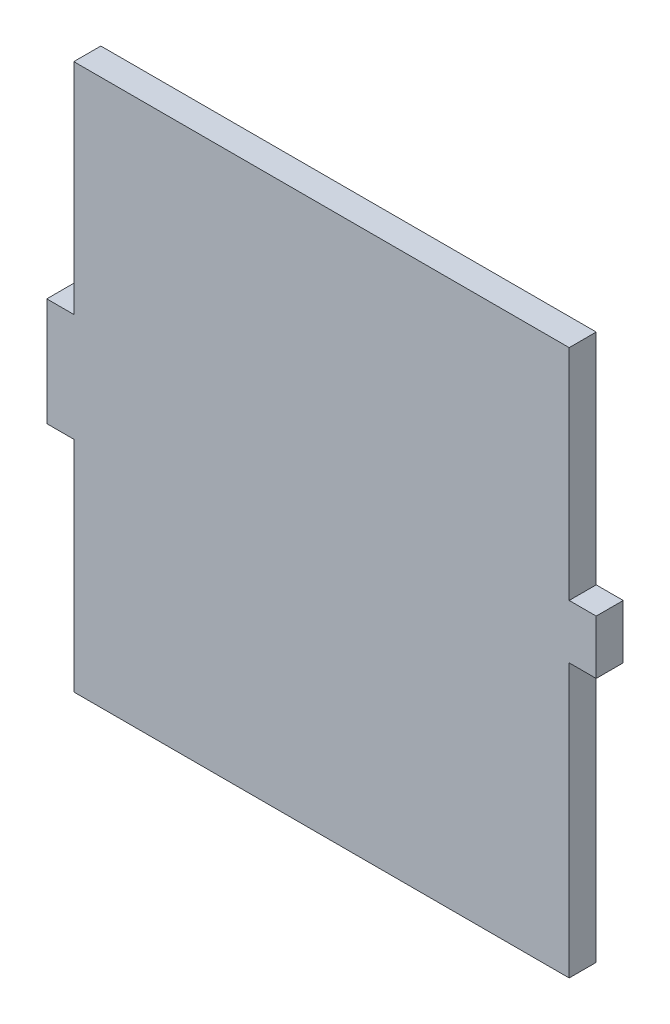
SolidWorks part; units mm, degrees
ref_plane "Přední rovina" through (0, 0, 0) normal (0, 0, 1) x (1, 0, 0)
ref_plane "Horní rovina" through (0, 0, 0) normal (0, 1, 0) x (1, 0, 0)
ref_plane "Pravá rovina" through (0, 0, 0) normal (1, 0, 0) x (0, 0, -1)
sketch "Skica1" plane through (0, 0, 0) normal (0, 0, 1) x (1, 0, 0)
  line L4 (55, -30.31) -> (55, -60.61)
  line L23 (0, 0) -> (55, 0)
  line L24 (0, 0) -> (0, -24.31)
  line L25 (0, -60.61) -> (55, -60.61)
  line L26 (55, 0) -> (55, -24.31)
  line L27 (0, -24.31) -> (-3, -24.31)
  line L29 (0, -36.31) -> (-3, -36.31)
  line L30 (-3, -24.31) -> (-3, -36.31)
  line L31 (55, -24.31) -> (58, -24.31)
  line L33 (55, -30.31) -> (58, -30.31)
  line L34 (58, -24.31) -> (58, -30.31)
  line L35 (0, -36.31) -> (0, -60.61)
  dimension "D1" = 55
  dimension "D2" = 60.61
  dimension "D3" = 24.31
  dimension "D4" = 0
  dimension "D5" = 6
  dimension "D6" = 12
  dimension "D7" = 3
  dimension "D8" = 3
extrude "Přidat vysunutím1" add sketch "Skica1" along normal blind 3
